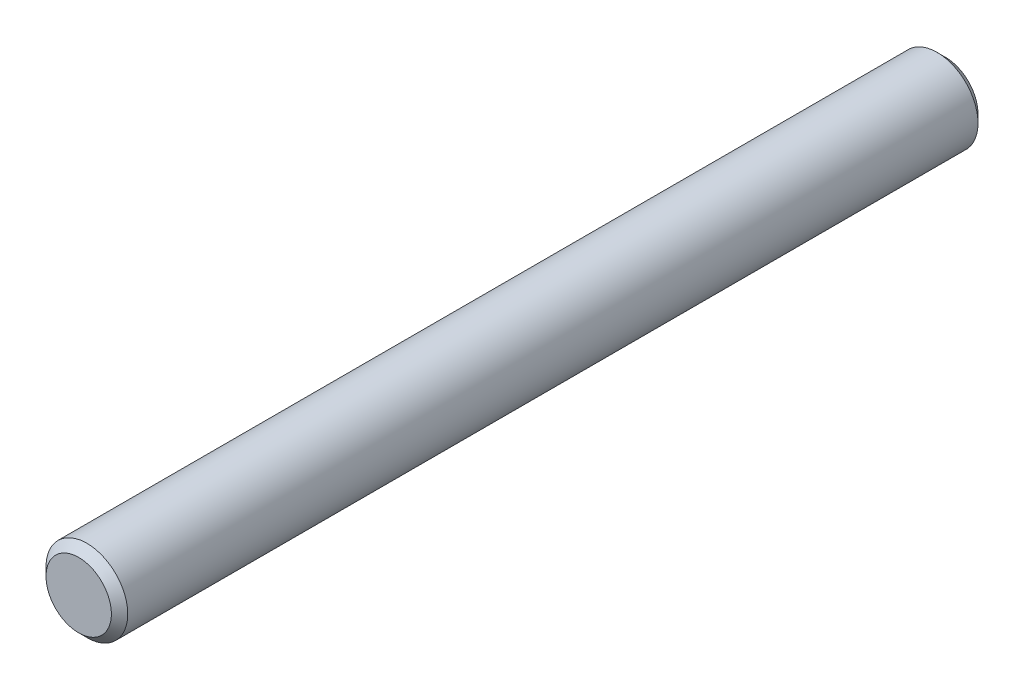
SolidWorks part; units mm, degrees
ref_plane "前视基准面" through (0, 0, 0) normal (0, 0, 1) x (1, 0, 0)
ref_plane "上视基准面" through (0, 0, 0) normal (0, 1, 0) x (1, 0, 0)
ref_plane "右视基准面" through (0, 0, 0) normal (1, 0, 0) x (0, 0, -1)
sketch "草图1" plane through (0, 0, 0) normal (0, 0, 1) x (1, 0, 0)
  circle A0 centre (0, 0) radius 0.5
  dimension "D1" = 1
extrude "凸台-拉伸1" add sketch "草图1" along normal blind 10 and the other way blind 1
chamfer "倒角1" distance 0.1 angle 45 2 edges at (0.5, 0, 10) (0.5, 0, -1)
ref_plane "基准面1" through (0, 0, -0.1404) normal (0, 0, -1) x (-1, 0, 0)
sketch "草图2" plane through (0, 0, -0.1404) normal (0, 0, -1) x (-1, 0, 0)
  circle A0 centre (0, 0) radius 0.6
  dimension "D1" = 1.2
sketch "草图3" plane through (0, 0, -1) normal (0, 0, -1) x (-1, 0, 0)
  circle A0 centre (0, 0) radius 0.5
  circle A1 centre (0, 0) radius 0.5 construction
extrude "切除-拉伸1" cut sketch "草图3" against normal blind 0.4
chamfer "倒角2" distance 0.1 angle 45 1 edges at (-0.5, 0, -0.6)
